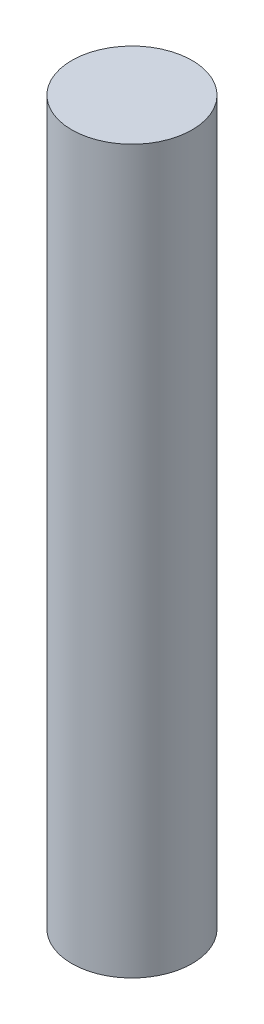
SolidWorks part; units mm, degrees
material "镀铬不锈钢"
ref_plane "前视基准面" through (0, 0, 0) normal (0, 0, 1) x (1, 0, 0)
ref_plane "上视基准面" through (0, 0, 0) normal (0, 1, 0) x (1, 0, 0)
ref_plane "右视基准面" through (0, 0, 0) normal (1, 0, 0) x (0, 0, -1)
sketch "草图1" plane through (0, 0, 0) normal (0, 1, 0) x (1, 0, 0)
  circle A0 centre (0, 0) radius 2.5
  dimension "D1" = 5
extrude "凸台-拉伸1" add sketch "草图1" along normal blind 30
